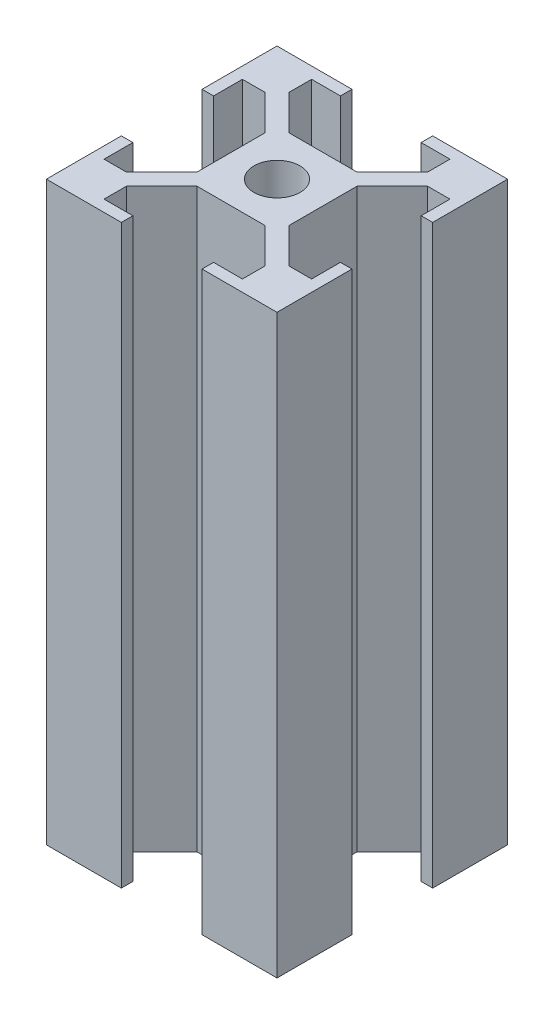
SolidWorks part; units mm, degrees
ref_plane "Front Plane" through (0, 0, 0) normal (0, 0, 1) x (1, 0, 0)
ref_plane "Top Plane" through (0, 0, 0) normal (0, 1, 0) x (1, 0, 0)
ref_plane "Right Plane" through (0, 0, 0) normal (1, 0, 0) x (0, 0, -1)
sketch "Sketch1" plane through (0, 0, 0) normal (0, 1, 0) x (1, 0, 0)
  line L1 (-20, -20) -> (20, -20)
  line L2 (-20, -20) -> (-20, 20)
  line L3 (-20, 20) -> (20, 20)
  line L4 (20, -20) -> (20, 20)
  line L5 (-20, -20) -> (20, 20) construction
  line L6 (-20, 20) -> (20, -20) construction
  point P0 (0, 0)
  dimension "D1" = 40
  dimension "D2" = 40
extrude "Boss-Extrude1" add sketch "Sketch1" along normal blind 100
sketch "Sketch2" plane through (0, 100, 0) normal (0, 1, 0) x (1, 0, 0)
  line L0 (0, 20) -> (0, -20) construction
  line L1 (20, 20) -> (-20, 20) construction
  line L2 (-20, -20) -> (20, -20) construction
  line L3 (-7, 20) -> (-7, 18)
  line L4 (-7, 18) -> (-12, 18)
  line L5 (-12, 18) -> (-12, 14.1213)
  line L6 (-12, 14.1213) -> (-5.8787, 8)
  line L7 (-5.8787, 8) -> (5.8787, 8)
  line L8 (-20, 20) -> (0, 0) construction
  line L9 (12, 14.1213) -> (5.8787, 8)
  line L10 (12, 18) -> (12, 14.1213)
  line L11 (7, 18) -> (12, 18)
  line L12 (7, 20) -> (7, 18)
  line L13 (20, 7) -> (18, 7)
  line L14 (18, 7) -> (18, 12)
  line L15 (18, 12) -> (14.1213, 12)
  line L16 (14.1213, 12) -> (8, 5.8787)
  line L17 (8, 5.8787) -> (8, -5.8787)
  line L18 (14.1213, -12) -> (8, -5.8787)
  line L19 (18, -12) -> (14.1213, -12)
  line L20 (18, -7) -> (18, -12)
  line L21 (20, -7) -> (18, -7)
  line L22 (7, -20) -> (7, -18)
  line L23 (7, -18) -> (12, -18)
  line L24 (12, -18) -> (12, -14.1213)
  line L25 (12, -14.1213) -> (5.8787, -8)
  line L26 (5.8787, -8) -> (-5.8787, -8)
  line L27 (-12, -14.1213) -> (-5.8787, -8)
  line L28 (-12, -18) -> (-12, -14.1213)
  line L29 (-7, -18) -> (-12, -18)
  line L30 (-7, -20) -> (-7, -18)
  line L31 (-20, -7) -> (-18, -7)
  line L32 (-18, -7) -> (-18, -12)
  line L33 (-18, -12) -> (-14.1213, -12)
  line L34 (-14.1213, -12) -> (-8, -5.8787)
  line L35 (-8, -5.8787) -> (-8, 5.8787)
  line L36 (-14.1213, 12) -> (-8, 5.8787)
  line L37 (-18, 12) -> (-14.1213, 12)
  line L38 (-18, 7) -> (-18, 12)
  line L39 (-20, 7) -> (-18, 7)
  line L40 (-20, 7) -> (-20, -7)
  line L41 (-7, 20) -> (7, 20)
  line L42 (20, 7) -> (20, -7)
  line L43 (-7, -20) -> (7, -20)
  circle A0 centre (0, 0) radius 4
  point P16 (0, 8)
  point P22 (0, 8)
  point P56 (0, 0)
  dimension "D7" = 8
  dimension "D1" = 7
  dimension "D2" = 12
  dimension "D3" = 2
  dimension "D4" = 5
  dimension "D5" = 1.5
  dimension "D6" = 4
extrude "Cut-Extrude1" cut sketch "Sketch2" against normal through all both and the other way through all
